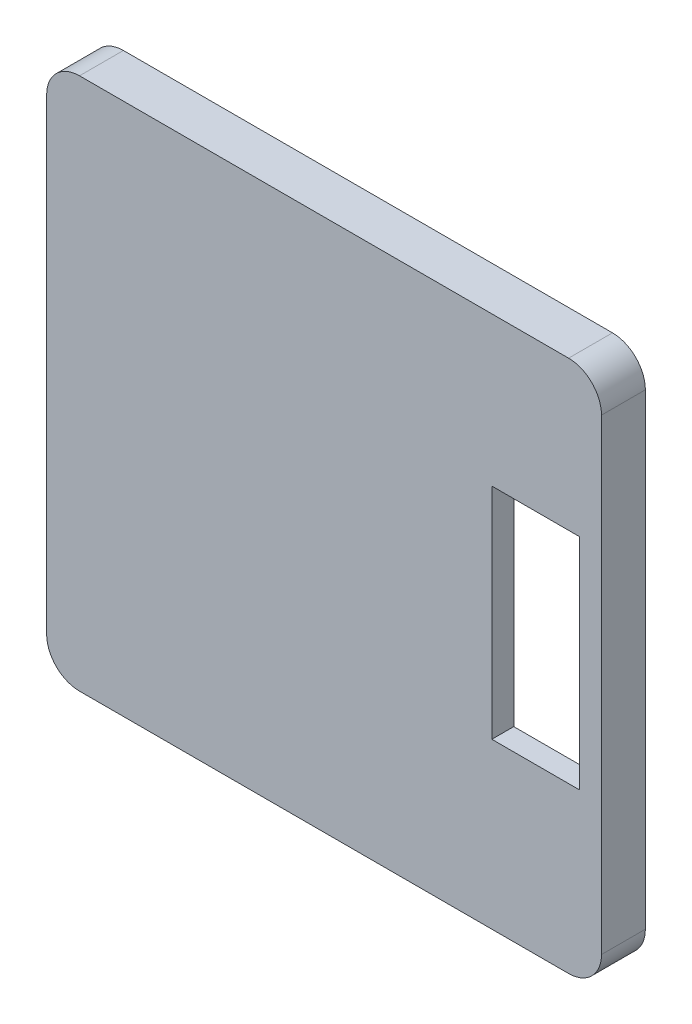
SolidWorks part; units mm, degrees
material "ABS"
ref_plane "Front Plane" through (0, 0, 0) normal (0, 0, 1) x (1, 0, 0)
ref_plane "Top Plane" through (0, 0, 0) normal (0, 1, 0) x (1, 0, 0)
ref_plane "Right Plane" through (0, 0, 0) normal (1, 0, 0) x (0, 0, -1)
sketch "Sketch1" plane through (0, 0, 0) normal (0, 0, 1) x (1, 0, 0)
  line L0 (-22.7552, 21.8828) -> (22.2448, 21.8828)
  line L1 (-22.7552, 21.8828) -> (-22.7552, -18.1172)
  line L2 (-22.7552, -18.1172) -> (22.2448, -18.1172)
  line L3 (-22.5552, -23.9172) -> (22.0448, -23.9172)
  line L4 (25.0448, -20.9172) -> (25.0448, 21.6828)
  line L5 (22.0448, 24.6828) -> (-22.5552, 24.6828)
  line L6 (-25.5552, 21.6828) -> (-25.5552, -20.9172)
  line L7 (22.2448, 21.8828) -> (22.2448, -18.1172)
  arc A0 (-25.5552, -20.9172) -> (-22.5552, -23.9172) centre (-22.5552, -20.9172) ccw
  arc A1 (22.0448, -23.9172) -> (25.0448, -20.9172) centre (22.0448, -20.9172) ccw
  arc A2 (25.0448, 21.6828) -> (22.0448, 24.6828) centre (22.0448, 21.6828) ccw
  arc A3 (-22.5552, 24.6828) -> (-25.5552, 21.6828) centre (-22.5552, 21.6828) ccw
extrude "Boss-Extrude1" add sketch "Sketch1" along normal mid plane 4
sketch "Sketch2" plane through (-22.7552, 0, 0) normal (1, 0, 0) x (0, 0, -1)
  line L0 (-2, -20.9172) -> (2, -20.9172) construction
  line L1 (-2, 21.8828) -> (0, 21.8828)
  line L2 (-2, 21.8828) -> (-2, -20.9172)
  line L3 (-2, -20.9172) -> (0, -20.9172)
  line L4 (0, 21.8828) -> (0, -20.9172)
  line L6 (-2, 21.8828) -> (2, 21.8828) construction
  dimension "D1" = 2
extrude "Boss-Extrude2" add sketch "Sketch2" along normal up to surface (45 mm away) up to face at (22.2448, 1.8828, 0)
fillet "Fillet1" radius 1 8 edges at (22.2448, -18.1172, -1) (-0.2552, -18.1172, 0) (-22.7552, -18.1172, -1) (-22.7552, 21.8828, -1) (-22.7552, 1.8828, 0) (22.2448, 21.8828, -1) (-0.2552, 21.8828, 0) (22.2448, 1.8828, 0)
sketch "Sketch3" plane through (-25.5552, 0, 0) normal (-1, 0, 0) x (0, 0, 1)
  line L0 (-2, 21.6828) -> (-2, -20.9172) construction
  line L1 (-2, 6.0828) -> (0, 6.0828)
  line L2 (-2, 6.0828) -> (-2, -6.9172)
  line L3 (-2, -6.9172) -> (0, -6.9172)
  line L4 (0, 6.0828) -> (0, -6.9172)
  line L5 (2, -23.9172) -> (-2, -23.9172) construction
  point P8 (0, -23.9172)
  dimension "D1" = 17
  dimension "D2" = 13
  dimension "D3" = 2
extrude "Cut-Extrude1" cut sketch "Sketch3" against normal blind 11
sketch "Sketch4" plane through (0, 0, 2) normal (0, 0, 1) x (1, 0, 0)
  line L0 (25.0448, 0.3828) -> (23.0448, 0.3828) construction
  line L1 (25.0448, -20.9172) -> (25.0448, 21.6828) construction
  line L2 (-22.5552, -23.9172) -> (22.0448, -23.9172) construction
  line L3 (23.0448, -8.9172) -> (15.0448, -8.9172)
  line L4 (23.0448, -8.9172) -> (23.0448, 11.0828)
  line L5 (23.0448, 11.0828) -> (15.0448, 11.0828)
  line L6 (15.0448, -8.9172) -> (15.0448, 11.0828)
  dimension "D1" = 2
  dimension "D2" = 15
  dimension "D3" = 20
  dimension "D4" = 8
extrude "Cut-Extrude2" cut sketch "Sketch4" against normal blind 11
